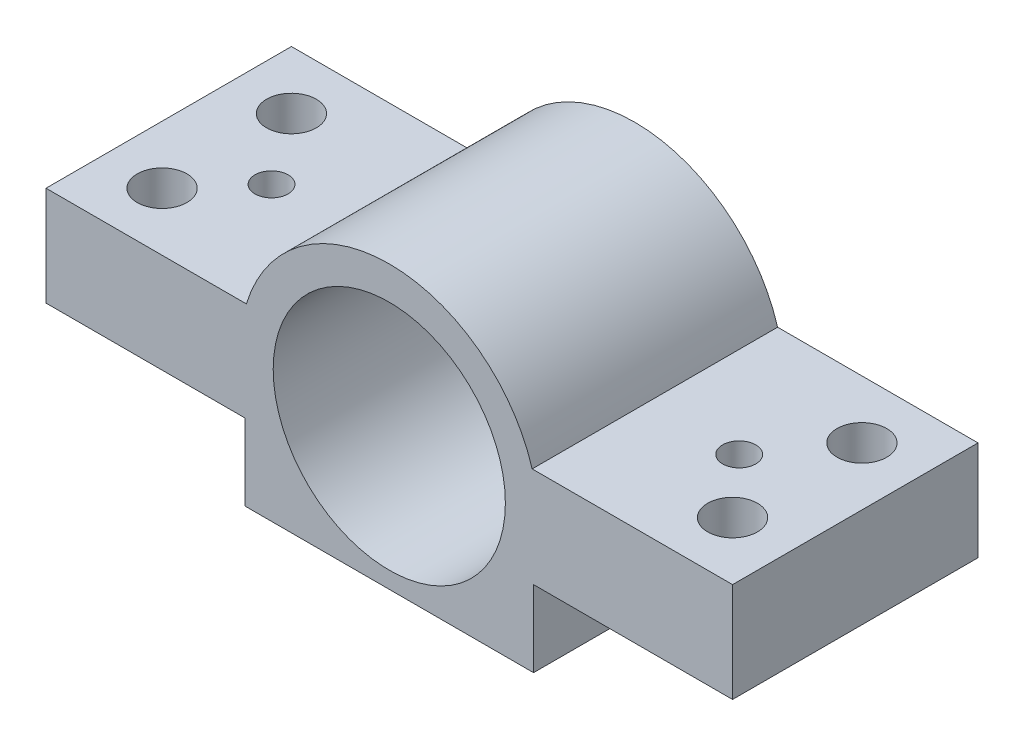
SolidWorks part; units mm, degrees
ref_plane "前视基准面" through (0, 0, 0) normal (0, 0, 1) x (1, 0, 0)
ref_plane "上视基准面" through (0, 0, 0) normal (0, 1, 0) x (1, 0, 0)
ref_plane "右视基准面" through (0, 0, 0) normal (1, 0, 0) x (0, 0, -1)
sketch "草图1" plane through (0, 0, 0) normal (0, 0, 1) x (1, 0, 0)
  line L0 (-43.5, 0) -> (43.5, 0)
  line L1 (55, 0) -> (-55, 0) construction
  line L3 (43.5, 0) -> (43.5, 23)
  line L4 (43.5, 23) -> (103.5, 23)
  line L5 (103.5, 23) -> (103.5, 53)
  line L6 (0, -55) -> (0, 55) construction
  line L7 (-43.5, 0) -> (-43.5, 23)
  line L8 (-43.5, 23) -> (-103.5, 23)
  line L9 (-103.5, 23) -> (-103.5, 53)
  line L10 (-103.5, 53) -> (-43.0813, 53)
  line L11 (103.5, 53) -> (43.0813, 53)
  arc A0 (43.0813, 53) -> (-43.0813, 53) centre (0, 40) ccw
  circle A1 centre (0, 40) radius 35
  point P6 (0, 0)
  dimension "D1" = 70
  dimension "D2" = 90
  dimension "D3" = 40
  dimension "D4" = 87
  dimension "D5" = 23
  dimension "D6" = 30
  dimension "D7" = 60
  dimension "D8" = 23
  dimension "D9" = 60
  dimension "D10" = 30
extrude "凸台-拉伸1" add sketch "草图1" along normal blind 74
sketch "草图2" plane through (0, 0, 0) normal (0, 0, -1) x (-1, 0, 0)
  circle A0 centre (0, 40) radius 35
  circle A1 centre (0, 40) radius 21
  dimension "D1" = 42
extrude "凸台-拉伸2" add sketch "草图2" against normal blind 13
sketch "草图3" plane through (0, 23, 0) normal (0, -1, 0) x (1, 0, 0)
  circle A0 centre (-86, 56.5) radius 7.5
  circle A1 centre (-70.5, 39) radius 5
  circle A2 centre (-86, 17.5) radius 7.5
  circle A3 centre (86, 56.5) radius 7.5
  circle A4 centre (70.5, 39) radius 5
  circle A5 centre (86, 17.5) radius 7.5
extrude "切除-拉伸1" cut sketch "草图3" against normal up to surface (30 mm away) up to face at (73.2907, 53, 37)
